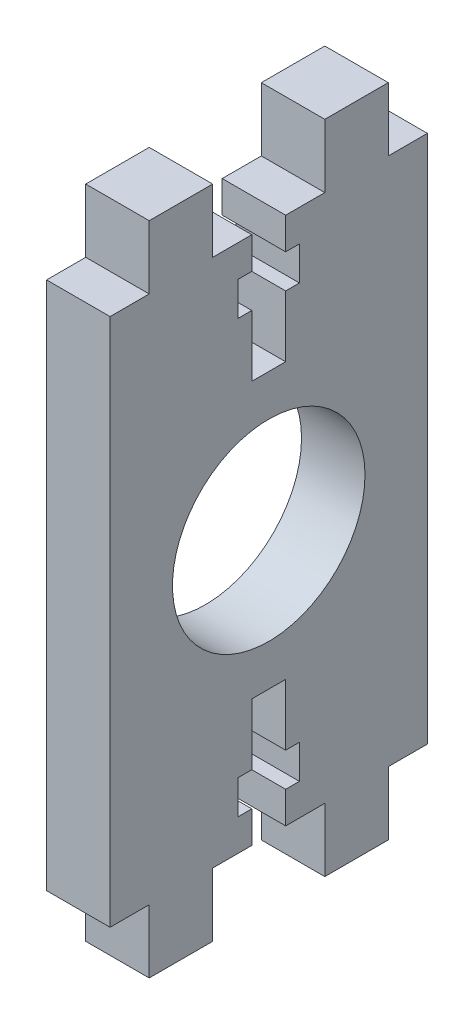
SolidWorks part; units mm, degrees
material "Oak"
ref_plane "Front Plane" through (0, 0, 0) normal (0, 0, 1) x (1, 0, 0)
ref_plane "Top Plane" through (0, 0, 0) normal (0, 1, 0) x (1, 0, 0)
ref_plane "Right Plane" through (0, 0, 0) normal (1, 0, 0) x (0, 0, -1)
sketch "Sketch1" plane through (0, 0, 0) normal (1, 0, 0) x (0, 0, -1)
  line L0 (-15, -25) -> (-15, 25)
  line L1 (-15, 25) -> (-11.3, 25)
  line L2 (-1.6, 25) -> (-1.6, 22)
  line L3 (-1.6, 22) -> (-2.9, 22)
  line L4 (-2.9, 22) -> (-2.9, 18.8)
  line L5 (-2.9, 18.8) -> (-1.6, 18.8)
  line L6 (-1.6, 18.8) -> (-1.6, 13)
  line L7 (-1.6, 13) -> (1.6, 13)
  line L8 (1.6, 13) -> (1.6, 18.8)
  line L9 (1.6, 18.8) -> (2.9, 18.8)
  line L10 (2.9, 18.8) -> (2.9, 22)
  line L11 (2.9, 22) -> (1.6, 22)
  line L12 (1.6, 22) -> (1.6, 25)
  line L13 (1.6, 25) -> (5.3, 25)
  line L14 (15, 25) -> (15, -25)
  line L15 (-5.3, 25) -> (-1.6, 25)
  line L17 (-11.3, 25) -> (-11.3, 31)
  line L18 (-11.3, 31) -> (-5.3, 31)
  line L19 (-5.3, 25) -> (-5.3, 31)
  line L20 (0, 3.3) -> (0, -3.3) construction
  line L21 (5.3, 25) -> (5.3, 31)
  line L22 (11.3, 31) -> (5.3, 31)
  line L23 (11.3, 25) -> (11.3, 31)
  line L24 (11.3, 25) -> (15, 25)
  line L25 (3.3, 0) -> (-3.3, 0) construction
  line L26 (11.3, -25) -> (15, -25)
  line L27 (11.3, -25) -> (11.3, -31)
  line L28 (11.3, -31) -> (5.3, -31)
  line L29 (5.3, -25) -> (5.3, -31)
  line L30 (-5.3, -25) -> (-5.3, -31)
  line L31 (-11.3, -31) -> (-5.3, -31)
  line L32 (-11.3, -25) -> (-11.3, -31)
  line L33 (-5.3, -25) -> (-1.6, -25)
  line L34 (1.6, -25) -> (5.3, -25)
  line L35 (1.6, -22) -> (1.6, -25)
  line L36 (2.9, -22) -> (1.6, -22)
  line L37 (2.9, -18.8) -> (2.9, -22)
  line L38 (1.6, -18.8) -> (2.9, -18.8)
  line L39 (1.6, -13) -> (1.6, -18.8)
  line L40 (-1.6, -13) -> (1.6, -13)
  line L41 (-1.6, -18.8) -> (-1.6, -13)
  line L42 (-2.9, -18.8) -> (-1.6, -18.8)
  line L43 (-2.9, -22) -> (-2.9, -18.8)
  line L44 (-1.6, -22) -> (-2.9, -22)
  line L45 (-1.6, -25) -> (-1.6, -22)
  line L46 (-15, -25) -> (-11.3, -25)
  circle A0 centre (0, 0) radius 9.1
  point P44 (15, 0)
  point P56 (-15, 0)
  dimension "D1" = 18.2
  dimension "D3" = 3.2
  dimension "D4" = 25
  dimension "D5" = 3.2
  dimension "D6" = 5.8
  dimension "D7" = 3
  dimension "D8" = 18
  dimension "D9" = 6
  dimension "D10" = 6
  dimension "D2" = 30
extrude "Boss-Extrude1" add sketch "Sketch1" along normal blind 6
